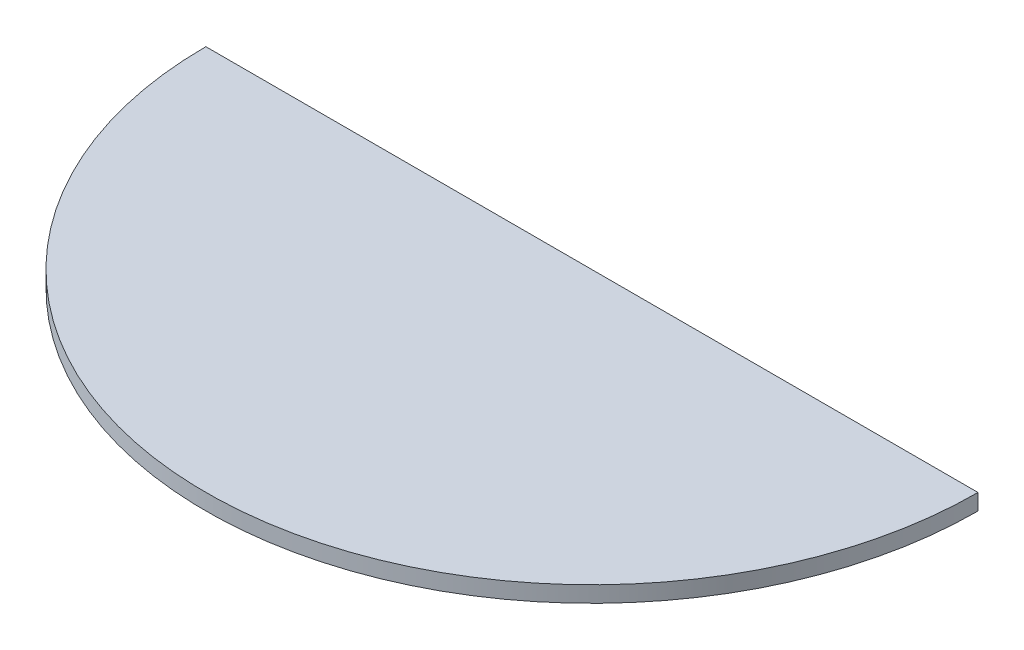
SolidWorks part; units mm, degrees
material "ABS"
ref_plane "Front Plane" through (0, 0, 0) normal (0, 0, 1) x (1, 0, 0)
ref_plane "Top Plane" through (0, 0, 0) normal (0, 1, 0) x (1, 0, 0)
ref_plane "Right Plane" through (0, 0, 0) normal (1, 0, 0) x (0, 0, -1)
other "Bounding Box"
ref_plane "Default Plane" through (-152.4, 6.35, 0) normal (0, 0, 1) x (1, 0, 0)
sketch "Sketch1" plane through (0, 0, 0) normal (0, 1, 0) x (1, 0, 0)
  line L0 (-152.4, 0) -> (152.4, 0)
  arc A0 (-152.4, 0) -> (152.4, 0) centre (0, 0) cw
  point P0 (0, 0)
  dimension "D1" = 304.8
sketch "Sketch2" plane through (0, 0, 0) normal (0, 0, 1) x (1, 0, 0)
  line L3 (-152.4, 0) -> (0, 0)
  line L10 (-152.4, 0) -> (-152.4, 6.35)
  line L11 (0, 0) -> (0, 6.35)
  line L12 (-152.4, 6.35) -> (0, 6.35)
  line L13 (-152.4, 0) -> (152.4, 0) construction
  line L14 (152.4, 0) -> (-152.4, 0) construction
  dimension "D1" = 6.35
revolve "Revolve1" add sketch "Sketch2" angle 180 about L11
